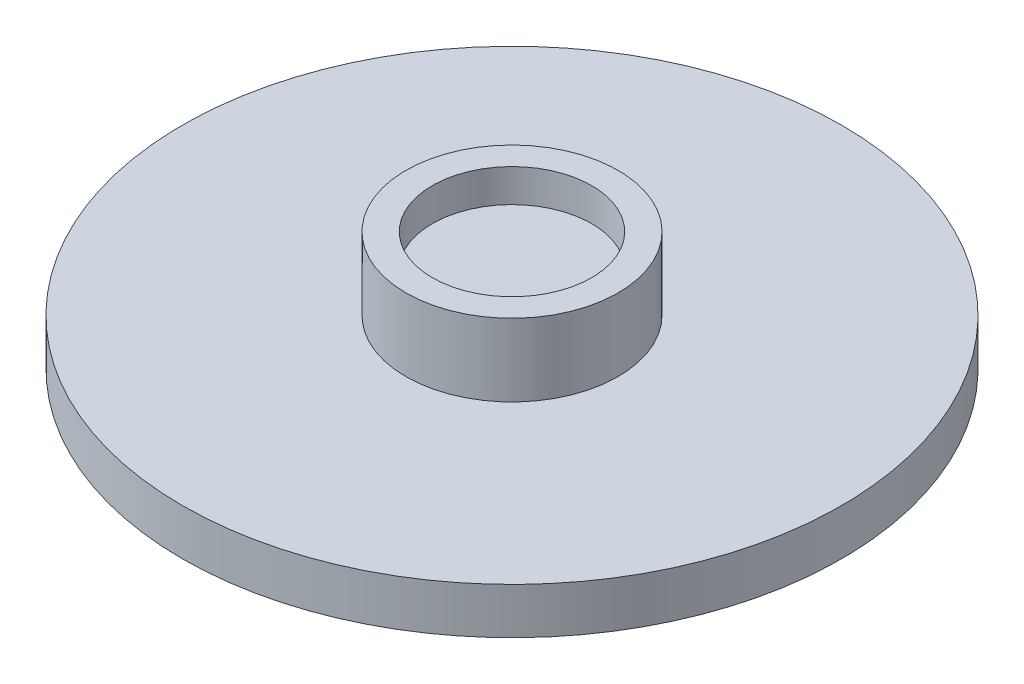
SolidWorks part; units mm, degrees
ref_plane "Front Plane" through (0, 0, 0) normal (0, 0, 1) x (1, 0, 0)
ref_plane "Top Plane" through (0, 0, 0) normal (0, 1, 0) x (1, 0, 0)
ref_plane "Right Plane" through (0, 0, 0) normal (1, 0, 0) x (0, 0, -1)
sketch "Sketch1" plane through (0, 0, 0) normal (0, 1, 0) x (1, 0, 0)
  circle A0 centre (0, 0) radius 25
  dimension "D1" = 50
extrude "Boss-Extrude1" add sketch "Sketch1" along normal blind 3.5
sketch "Sketch2" plane through (0, 3.5, 0) normal (0, 1, 0) x (1, 0, 0)
  circle A0 centre (0, 0) radius 6.05
  circle A1 centre (0, 0) radius 8.05
  dimension "D1" = 12.1
  dimension "D2" = 16.1
extrude "Boss-Extrude2" add sketch "Sketch2" along normal blind 5.5
sketch "Sketch3" plane through (0, 3.5, 0) normal (0, 1, 0) x (1, 0, 0)
  circle A0 centre (0, 0) radius 6.15
extrude "Boss-Extrude3" add sketch "Sketch3" along normal blind 3
